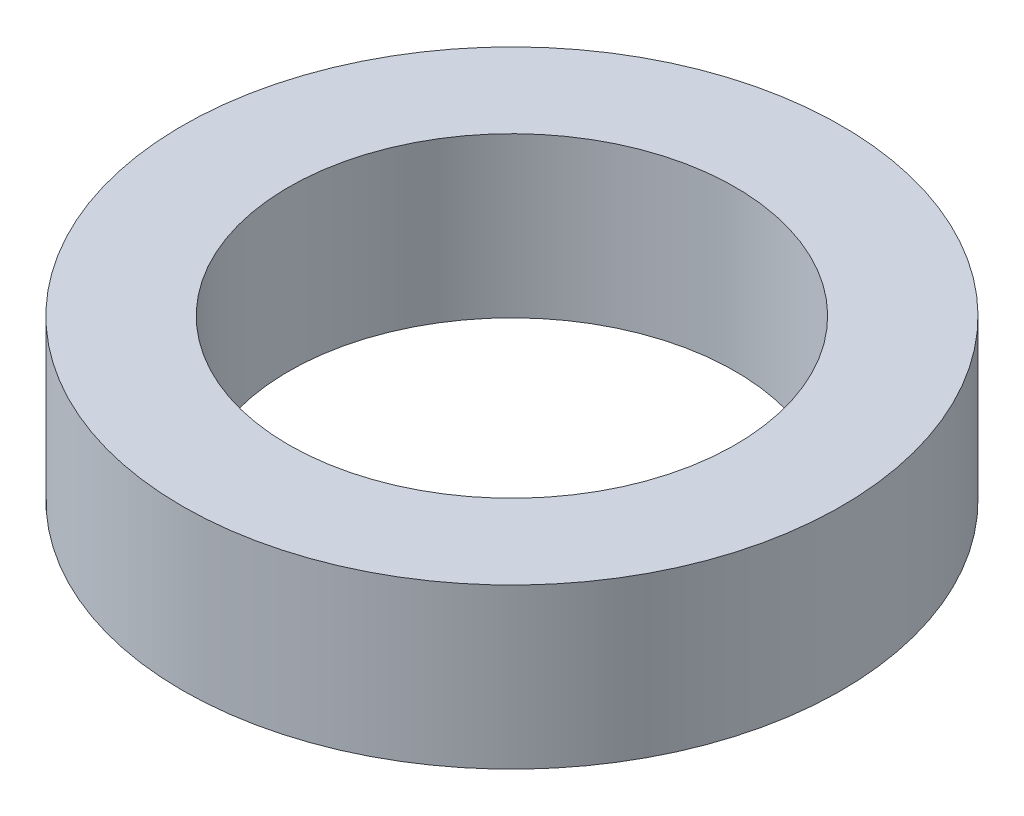
SolidWorks part; units mm, degrees
ref_plane "前视基准面" through (0, 0, 0) normal (0, 0, 1) x (1, 0, 0)
ref_plane "上视基准面" through (0, 0, 0) normal (0, 1, 0) x (1, 0, 0)
ref_plane "右视基准面" through (0, 0, 0) normal (1, 0, 0) x (0, 0, -1)
sketch "草图1" plane through (0, 0, 0) normal (0, 1, 0) x (1, 0, 0)
  circle A0 centre (0, 0) radius 2.1
  circle A1 centre (0, 0) radius 3.1
  dimension "D1" = 4.2
  dimension "D2" = 1
extrude "凸台-拉伸1" add sketch "草图1" along normal blind 1.5
